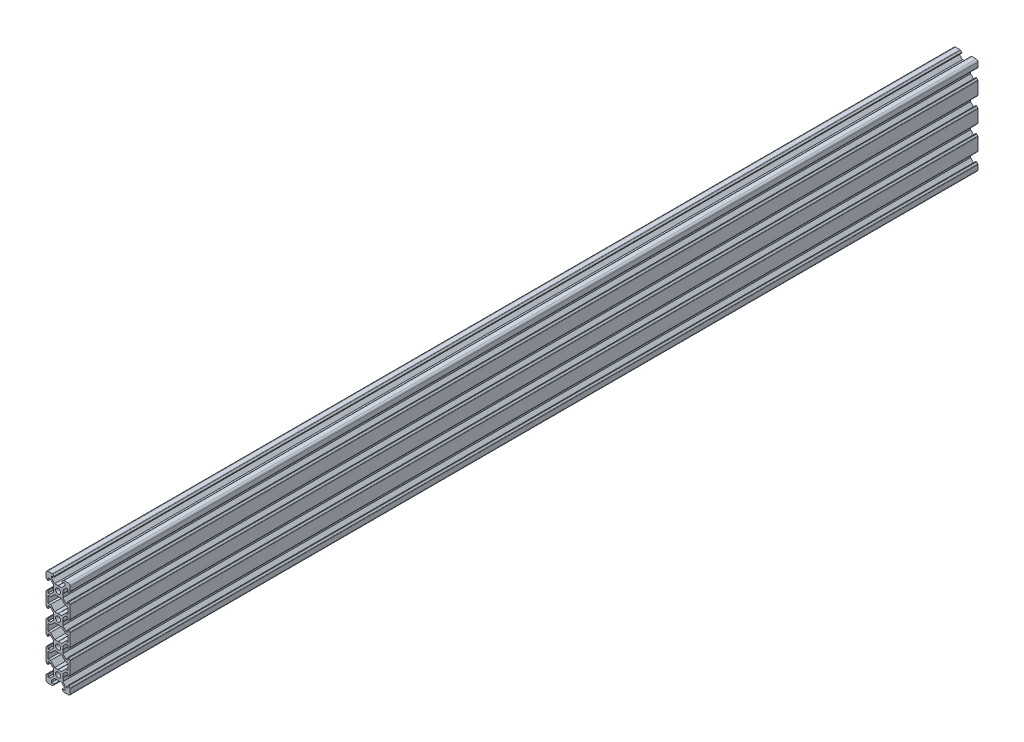
SolidWorks part; units mm, degrees
material "6063-T5"
ref_plane "Front" through (0, 0, 0) normal (0, 0, 1) x (1, 0, 0)
ref_plane "Top" through (0, 0, 0) normal (0, 1, 0) x (1, 0, 0)
ref_plane "Right" through (0, 0, 0) normal (1, 0, 0) x (0, 0, -1)
sketch "Sketch1" plane through (0, 0, 0) normal (0, 0, 1) x (1, 0, 0)
  line L0 (-8.5, 10) -> (-10, 8.5) construction
  line L1 (-8.5, 10) -> (-4.8628, 10)
  line L2 (-10, 8.5) -> (-10, 4.8628)
  line L3 (-2.8395, -23.9005) -> (-0.1, -23.9005)
  line L4 (10, 8.5) -> (10, 4.8628)
  line L5 (-10, 10) -> (10, -10) construction
  line L6 (-10, -10) -> (10, 10) construction
  line L7 (8.2, -5.5) -> (8.2, -3.3865)
  line L8 (-8.2, -5.5) -> (-8.2, -3.3865)
  line L9 (-5.5, 8.2) -> (-3.3865, 8.2)
  line L10 (-8.2, -12.7) -> (-8.2, -7.3)
  line L11 (-3.9005, 2.8395) -> (-6.561, 5.5)
  line L12 (-6.561, 5.5) -> (-8.2, 5.5)
  line L13 (-2.8395, -3.9005) -> (-0.1, -3.9005)
  line L14 (-3.9005, -2.8395) -> (-3.9005, -0.1)
  line L15 (-2.8395, 3.9005) -> (-0.1, 3.9005)
  line L16 (3.9005, -2.8395) -> (3.9005, -0.1)
  line L17 (-8.2, 3.3865) -> (-8.81, 3.3865)
  line L18 (-8.81, 3.3865) -> (-9.7976, 4.3741)
  line L19 (8.5, 10) -> (10, 8.5) construction
  line L20 (-2.8395, 3.9005) -> (-5.5, 6.561)
  line L21 (-5.5, 6.561) -> (-5.5, 8.2)
  line L22 (-3.3865, 8.2) -> (-3.3865, 8.81)
  line L23 (-3.3865, 8.81) -> (-4.3741, 9.7976)
  line L24 (0, 24.069) -> (0, -84.2588) construction
  line L25 (3.3865, 8.81) -> (4.3741, 9.7976)
  line L26 (3.3865, 8.2) -> (3.3865, 8.81)
  line L27 (5.5, 6.561) -> (5.5, 8.2)
  line L28 (2.8395, 3.9005) -> (5.5, 6.561)
  line L29 (3.3865, 8.2) -> (5.5, 8.2)
  line L30 (4.8628, 10) -> (8.5, 10)
  line L31 (-0.1, 3.9005) -> (0, 3.8005)
  line L32 (0.1, 3.9005) -> (0, 3.8005)
  line L33 (0.1, 3.9005) -> (2.8395, 3.9005)
  line L34 (25.9287, 0) -> (-28.3459, 0) construction
  line L35 (-0.1, -3.9005) -> (0, -3.8005)
  line L36 (0.1, -3.9005) -> (0, -3.8005)
  line L37 (0.1, -3.9005) -> (2.8395, -3.9005)
  line L38 (-3.9005, 0.1) -> (-3.8005, 0)
  line L39 (-3.8005, 0) -> (-3.9005, -0.1)
  line L40 (-3.9005, 0.1) -> (-3.9005, 2.8395)
  line L41 (3.9005, 0.1) -> (3.8005, 0)
  line L42 (3.8005, 0) -> (3.9005, -0.1)
  line L43 (3.9005, 0.1) -> (3.9005, 2.8395)
  line L44 (8.81, 3.3865) -> (9.7976, 4.3741)
  line L45 (8.2, 3.3865) -> (8.81, 3.3865)
  line L46 (6.561, 5.5) -> (8.2, 5.5)
  line L47 (3.9005, 2.8395) -> (6.561, 5.5)
  line L48 (2.8395, -3.9005) -> (5.5, -6.561)
  line L49 (3.9005, -2.8395) -> (6.561, -5.5)
  line L50 (-2.8395, -3.9005) -> (-5.5, -6.561)
  line L51 (-3.9005, -2.8395) -> (-6.561, -5.5)
  line L52 (6.561, -5.5) -> (8.2, -5.5)
  line L53 (-6.561, -5.5) -> (-8.2, -5.5)
  line L54 (-8.81, -3.3865) -> (-9.7976, -4.3741)
  line L55 (-8.2, -3.3865) -> (-8.81, -3.3865)
  line L56 (8.81, -3.3865) -> (9.7976, -4.3741)
  line L57 (8.2, -3.3865) -> (8.81, -3.3865)
  line L58 (8.2, 3.3865) -> (8.2, 5.5)
  line L59 (10, -4.8628) -> (10, -15.1372)
  line L60 (-8.2, 3.3865) -> (-8.2, 5.5)
  line L61 (25.9287, -10) -> (-24.6023, -10) construction
  line L62 (8.2, -12.7) -> (8.2, -7.3)
  line L63 (0.1, -23.9005) -> (2.8395, -23.9005)
  line L64 (-0.1, -23.9005) -> (0, -23.8005)
  line L65 (-3.9005, -22.8395) -> (-3.9005, -20.1)
  line L66 (0.1, -23.9005) -> (0, -23.8005)
  line L67 (-2.8395, -43.9005) -> (-0.1, -43.9005)
  line L68 (-3.8005, -20) -> (-3.9005, -20.1)
  line L69 (2.8395, -16.0995) -> (5.5, -13.439)
  line L70 (3.9005, -17.1605) -> (6.561, -14.5)
  line L71 (-3.9005, -19.9) -> (-3.8005, -20)
  line L72 (-3.9005, -19.9) -> (-3.9005, -17.1605)
  line L73 (3.9005, -22.8395) -> (6.561, -25.5)
  line L74 (5.5, -13.439) -> (6.239, -12.7)
  line L75 (-8.2, -14.5) -> (-8.2, -16.6135)
  line L76 (-8.2, -16.6135) -> (-8.81, -16.6135)
  line L77 (-8.81, -16.6135) -> (-9.7976, -15.6259)
  line L78 (8.81, -16.6135) -> (9.7976, -15.6259)
  line L79 (2.8395, -23.9005) -> (5.5, -26.561)
  line L80 (-2.8395, -16.0995) -> (-0.1, -16.0995)
  line L81 (0.1, -16.0995) -> (2.8395, -16.0995)
  line L82 (0.1, -16.0995) -> (0, -16.1995)
  line L83 (-0.1, -16.0995) -> (0, -16.1995)
  line L84 (-2.8395, -23.9005) -> (-5.5, -26.561)
  line L85 (8.2, -16.6135) -> (8.81, -16.6135)
  line L86 (8.2, -14.5) -> (8.2, -16.6135)
  line L87 (0.1, -43.9005) -> (2.8395, -43.9005)
  line L88 (-0.1, -43.9005) -> (0, -43.8005)
  line L89 (0.1, -43.9005) -> (0, -43.8005)
  line L90 (-2.8395, -63.9005) -> (-0.1, -63.9005)
  line L91 (0.1, -63.9005) -> (2.8395, -63.9005)
  line L92 (-0.1, -63.9005) -> (0, -63.8005)
  line L93 (0.1, -63.9005) -> (0, -63.8005)
  line L94 (-2.8395, -36.0995) -> (-0.1, -36.0995)
  line L95 (0.1, -36.0995) -> (2.8395, -36.0995)
  line L96 (0.1, -36.0995) -> (0, -36.1995)
  line L97 (-0.1, -36.0995) -> (0, -36.1995)
  line L98 (-2.8395, -56.0995) -> (-0.1, -56.0995)
  line L99 (0.1, -56.0995) -> (2.8395, -56.0995)
  line L100 (0.1, -56.0995) -> (0, -56.1995)
  line L101 (-0.1, -56.0995) -> (0, -56.1995)
  line L102 (3.9005, -22.8395) -> (3.9005, -20.1)
  line L103 (3.8005, -20) -> (3.9005, -20.1)
  line L104 (3.9005, -19.9) -> (3.8005, -20)
  line L105 (3.9005, -19.9) -> (3.9005, -17.1605)
  line L106 (-3.9005, -42.8395) -> (-3.9005, -40.1)
  line L107 (-3.8005, -40) -> (-3.9005, -40.1)
  line L108 (-3.9005, -39.9) -> (-3.8005, -40)
  line L109 (-3.9005, -39.9) -> (-3.9005, -37.1605)
  line L110 (3.9005, -42.8395) -> (3.9005, -40.1)
  line L111 (3.8005, -40) -> (3.9005, -40.1)
  line L112 (3.9005, -39.9) -> (3.8005, -40)
  line L113 (3.9005, -39.9) -> (3.9005, -37.1605)
  line L114 (-3.9005, -62.8395) -> (-3.9005, -60.1)
  line L115 (-6.239, -7.3) -> (-8.2, -7.3)
  line L116 (-5.5, -6.561) -> (-6.239, -7.3)
  line L117 (6.239, -7.3) -> (8.2, -7.3)
  line L118 (5.5, -6.561) -> (6.239, -7.3)
  line L119 (-6.239, -12.7) -> (-8.2, -12.7)
  line L120 (-2.8395, -16.0995) -> (-5.5, -13.439)
  line L121 (2.8395, -36.0995) -> (5.5, -33.439)
  line L122 (6.239, -12.7) -> (8.2, -12.7)
  line L123 (-10, -15.1372) -> (-10, -4.8628)
  line L124 (-3.8005, -60) -> (-3.9005, -60.1)
  line L125 (10, -24.8628) -> (10, -35.1372)
  line L126 (-3.9005, -59.9) -> (-3.8005, -60)
  line L127 (8.2, -30) -> (-28.3599, -30) construction
  line L128 (-3.9005, -59.9) -> (-3.9005, -57.1605)
  line L129 (3.9005, -62.8395) -> (3.9005, -60.1)
  line L130 (3.8005, -60) -> (3.9005, -60.1)
  line L131 (3.9005, -59.9) -> (3.8005, -60)
  line L132 (3.9005, -59.9) -> (3.9005, -57.1605)
  line L133 (-3.9005, -22.8395) -> (-6.561, -25.5)
  line L134 (-3.9005, -17.1605) -> (-6.561, -14.5)
  line L135 (3.9005, -37.1605) -> (6.561, -34.5)
  line L136 (3.9005, -42.8395) -> (6.561, -45.5)
  line L137 (-3.9005, -42.8395) -> (-6.561, -45.5)
  line L138 (-3.9005, -37.1605) -> (-6.561, -34.5)
  line L139 (3.9005, -57.1605) -> (6.561, -54.5)
  line L140 (3.9005, -62.8395) -> (6.561, -65.5)
  line L141 (-3.9005, -62.8395) -> (-6.561, -65.5)
  line L142 (-3.9005, -57.1605) -> (-6.561, -54.5)
  line L143 (2.8395, -43.9005) -> (5.5, -46.561)
  line L144 (-2.8395, -43.9005) -> (-5.5, -46.561)
  line L145 (-2.8395, -36.0995) -> (-5.5, -33.439)
  line L146 (2.8395, -56.0995) -> (5.5, -53.439)
  line L147 (2.8395, -63.9005) -> (5.5, -66.561)
  line L148 (-2.8395, -63.9005) -> (-5.5, -66.561)
  line L149 (-2.8395, -56.0995) -> (-5.5, -53.439)
  line L150 (-5.5, -13.439) -> (-6.239, -12.7)
  line L151 (6.561, -14.5) -> (8.2, -14.5)
  line L152 (-6.561, -14.5) -> (-8.2, -14.5)
  line L153 (10, -44.8628) -> (10, -55.1372)
  line L154 (-10, -35.1372) -> (-10, -24.8628)
  line L155 (8.2, -23.3865) -> (8.81, -23.3865)
  line L156 (8.81, -23.3865) -> (9.7976, -24.3741)
  line L157 (8.2, -25.5) -> (8.2, -23.3865)
  line L158 (8.2, -34.5) -> (8.2, -36.6135)
  line L159 (8.2, -36.6135) -> (8.81, -36.6135)
  line L160 (8.81, -36.6135) -> (9.7976, -35.6259)
  line L161 (-8.81, -36.6135) -> (-9.7976, -35.6259)
  line L162 (-8.2, -36.6135) -> (-8.81, -36.6135)
  line L163 (-8.2, -34.5) -> (-8.2, -36.6135)
  line L164 (-8.81, -23.3865) -> (-9.7976, -24.3741)
  line L165 (-8.2, -23.3865) -> (-8.81, -23.3865)
  line L166 (-8.2, -25.5) -> (-8.2, -23.3865)
  line L167 (-10, -55.1372) -> (-10, -44.8628)
  line L168 (8.2, -43.3865) -> (8.81, -43.3865)
  line L169 (8.81, -43.3865) -> (9.7976, -44.3741)
  line L170 (8.2, -45.5) -> (8.2, -43.3865)
  line L171 (8.2, -54.5) -> (8.2, -56.6135)
  line L172 (8.2, -56.6135) -> (8.81, -56.6135)
  line L173 (8.81, -56.6135) -> (9.7976, -55.6259)
  line L174 (-8.81, -56.6135) -> (-9.7976, -55.6259)
  line L175 (-8.2, -56.6135) -> (-8.81, -56.6135)
  line L176 (-8.2, -54.5) -> (-8.2, -56.6135)
  line L177 (-8.81, -43.3865) -> (-9.7976, -44.3741)
  line L178 (-8.2, -43.3865) -> (-8.81, -43.3865)
  line L179 (-8.2, -45.5) -> (-8.2, -43.3865)
  line L180 (-8.2, -32.7) -> (-8.2, -27.3)
  line L181 (8.2, -32.7) -> (8.2, -27.3)
  line L182 (6.239, -27.3) -> (8.2, -27.3)
  line L183 (6.239, -32.7) -> (8.2, -32.7)
  line L184 (-6.239, -32.7) -> (-8.2, -32.7)
  line L185 (-6.239, -27.3) -> (-8.2, -27.3)
  line L186 (-8.2, -52.7) -> (-8.2, -47.3)
  line L187 (8.2, -52.7) -> (8.2, -47.3)
  line L188 (6.239, -47.3) -> (8.2, -47.3)
  line L189 (6.239, -52.7) -> (8.2, -52.7)
  line L190 (-6.239, -52.7) -> (-8.2, -52.7)
  line L191 (-6.239, -47.3) -> (-8.2, -47.3)
  line L192 (5.5, -33.439) -> (6.239, -32.7)
  line L193 (-5.5, -33.439) -> (-6.239, -32.7)
  line L194 (6.561, -34.5) -> (8.2, -34.5)
  line L195 (-6.561, -34.5) -> (-8.2, -34.5)
  line L196 (6.561, -25.5) -> (8.2, -25.5)
  line L197 (5.5, -26.561) -> (6.239, -27.3)
  line L198 (-5.5, -26.561) -> (-6.239, -27.3)
  line L199 (-6.561, -25.5) -> (-8.2, -25.5)
  line L200 (5.5, -53.439) -> (6.239, -52.7)
  line L201 (-5.5, -53.439) -> (-6.239, -52.7)
  line L202 (6.561, -54.5) -> (8.2, -54.5)
  line L203 (-6.561, -54.5) -> (-8.2, -54.5)
  line L204 (6.561, -45.5) -> (8.2, -45.5)
  line L205 (5.5, -46.561) -> (6.239, -47.3)
  line L206 (-5.5, -46.561) -> (-6.239, -47.3)
  line L207 (-6.561, -45.5) -> (-8.2, -45.5)
  line L208 (-5.5, -66.561) -> (-5.5, -68.2)
  line L209 (5.5, -66.561) -> (5.5, -68.2)
  line L210 (3.3865, -68.2) -> (3.3865, -68.81)
  line L211 (3.3865, -68.2) -> (5.5, -68.2)
  line L212 (-5.5, -68.2) -> (-3.3865, -68.2)
  line L213 (-3.3865, -68.2) -> (-3.3865, -68.81)
  line L214 (-3.3865, -68.81) -> (-4.3741, -69.7976)
  line L215 (3.3865, -68.81) -> (4.3741, -69.7976)
  line L216 (-8.5, -70) -> (-4.8628, -70)
  line L217 (4.8628, -70) -> (8.5, -70)
  line L218 (6.561, -65.5) -> (8.2, -65.5)
  line L219 (-8.2, -63.3865) -> (-8.2, -65.5)
  line L220 (-6.561, -65.5) -> (-8.2, -65.5)
  line L221 (8.2, -63.3865) -> (8.2, -65.5)
  line L222 (8.2, -63.3865) -> (8.81, -63.3865)
  line L223 (-8.2, -63.3865) -> (-8.81, -63.3865)
  line L224 (-8.81, -63.3865) -> (-9.7976, -64.3741)
  line L225 (8.81, -63.3865) -> (9.7976, -64.3741)
  line L226 (-10, -68.5) -> (-10, -64.8628)
  line L227 (10, -68.5) -> (10, -64.8628)
  circle A0 centre (0, 0) radius 2.1
  arc A1 (-8.5, 10) -> (-10, 8.5) centre (-8.5, 8.5) ccw
  arc A2 (10, 8.5) -> (8.5, 10) centre (8.5, 8.5) ccw
  arc A3 (-4.3741, 9.7976) -> (-4.8628, 10) centre (-4.8628, 9.3088) ccw
  arc A4 (4.8628, 10) -> (4.3741, 9.7976) centre (4.8628, 9.3088) ccw
  circle A5 centre (0, -20) radius 2.1
  arc A6 (9.7976, 4.3741) -> (10, 4.8628) centre (9.3088, 4.8628) ccw
  arc A7 (-10, 4.8628) -> (-9.7976, 4.3741) centre (-9.3088, 4.8628) ccw
  arc A8 (-10, -4.8628) -> (-9.7976, -4.3741) centre (-9.3088, -4.8628) cw
  arc A9 (9.7976, -4.3741) -> (10, -4.8628) centre (9.3088, -4.8628) cw
  arc A10 (-10, -15.1372) -> (-9.7976, -15.6259) centre (-9.3088, -15.1372) ccw
  arc A11 (9.7976, -15.6259) -> (10, -15.1372) centre (9.3088, -15.1372) ccw
  circle A12 centre (0, -40) radius 2.1
  circle A13 centre (0, -60) radius 2.1
  arc A14 (9.7976, -24.3741) -> (10, -24.8628) centre (9.3088, -24.8628) cw
  arc A15 (9.7976, -35.6259) -> (10, -35.1372) centre (9.3088, -35.1372) ccw
  arc A16 (-10, -35.1372) -> (-9.7976, -35.6259) centre (-9.3088, -35.1372) ccw
  arc A17 (-10, -24.8628) -> (-9.7976, -24.3741) centre (-9.3088, -24.8628) cw
  arc A18 (9.7976, -44.3741) -> (10, -44.8628) centre (9.3088, -44.8628) cw
  arc A19 (9.7976, -55.6259) -> (10, -55.1372) centre (9.3088, -55.1372) ccw
  arc A20 (-10, -55.1372) -> (-9.7976, -55.6259) centre (-9.3088, -55.1372) ccw
  arc A21 (-10, -44.8628) -> (-9.7976, -44.3741) centre (-9.3088, -44.8628) cw
  arc A22 (10, -68.5) -> (8.5, -70) centre (8.5, -68.5) cw
  arc A23 (-8.5, -70) -> (-10, -68.5) centre (-8.5, -68.5) cw
  arc A24 (4.8628, -70) -> (4.3741, -69.7976) centre (4.8628, -69.3088) cw
  arc A25 (-4.3741, -69.7976) -> (-4.8628, -70) centre (-4.8628, -69.3088) cw
  arc A26 (9.7976, -64.3741) -> (10, -64.8628) centre (9.3088, -64.8628) cw
  arc A27 (-10, -64.8628) -> (-9.7976, -64.3741) centre (-9.3088, -64.8628) cw
  point P17 (-9.25, 9.25)
  point P21 (9.25, 9.25)
  dimension "D2" = 4.2
  dimension "D4" = 1.5
  dimension "D3" = 20
  dimension "D5" = 0.529
  dimension "D6" = 6.773
  dimension "D7" = 90
  dimension "D8" = 11
  dimension "D9" = 0.61
  dimension "D10" = 0.1
  dimension "D11" = 0.1
  dimension "D12" = 0.1
  dimension "D13" = 0.1
  dimension "D14" = 5.679
  dimension "D15" = 1.639
  dimension "D16" = 1.8
  dimension "D17" = 90
  dimension "D18" = 6.773
  dimension "D19" = 90
  dimension "D20" = 4
  dimension "D21" = 1.8
  dimension "D22" = 3
extrude "Boss-Extrude2" add sketch "Sketch1" along normal blind 750
